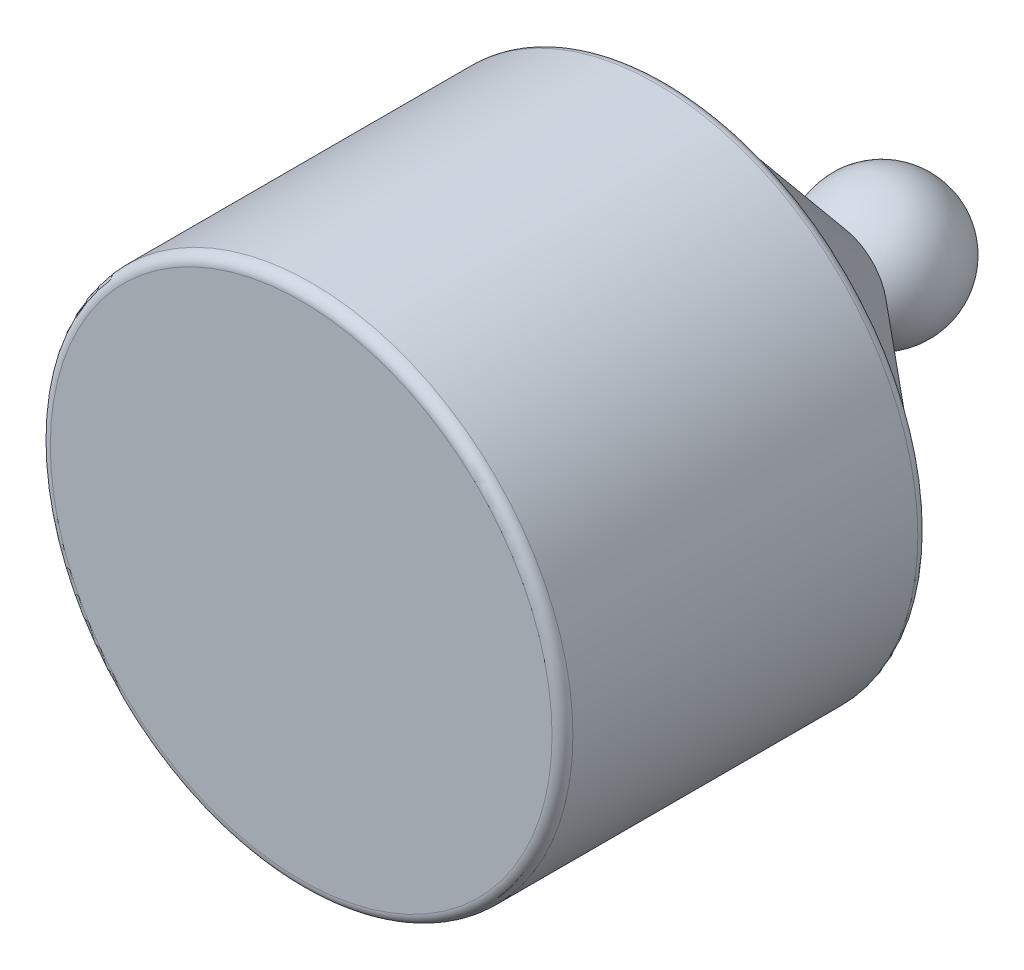
SolidWorks part; units mm, degrees
ref_plane "Front Plane" through (0, 0, 0) normal (0, 0, 1) x (1, 0, 0)
ref_plane "Top Plane" through (0, 0, 0) normal (0, 1, 0) x (1, 0, 0)
ref_plane "Right Plane" through (0, 0, 0) normal (1, 0, 0) x (0, 0, -1)
sketch "Sketch1" plane through (0, 0, 0) normal (0, 0, 1) x (1, 0, 0)
  circle A0 centre (0, 0) radius 5
extrude "Boss-Extrude1" add sketch "Sketch1" along normal blind 7
fillet "Fillet2" radius 0.2 1 edges at (5, 0, 7)
fillet "Fillet3" radius 0.2 1 edges at (5, 0, 0)
sketch "Sketch4" plane through (0, 0, 0) normal (0, 1, 0) x (1, 0, 0)
  line L0 (0, 5.422) -> (0, -10.0535) construction
  line L1 (4.8, 0) -> (0.9782, 3.2304)
  line L2 (0, 0) -> (4.8, 0)
  line L4 (0, 5.422) -> (0, 0)
  arc A0 (0.9782, 3.2304) -> (0, 5.422) centre (-0.0179, 4.0999) ccw
revolve "Revolve1" add sketch "Sketch4" angle 360 about L0
